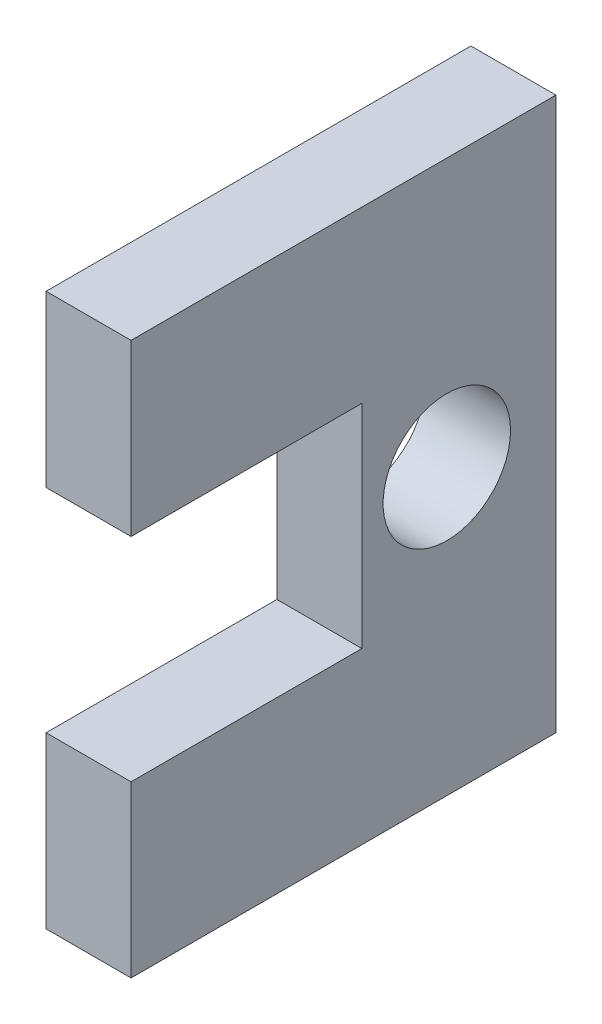
SolidWorks part; units mm, degrees
material "Perspex (TM) GS Acrylic Cast Sheet"
ref_plane "Front Plane" through (0, 0, 0) normal (0, 0, 1) x (1, 0, 0)
ref_plane "Top Plane" through (0, 0, 0) normal (0, 1, 0) x (1, 0, 0)
ref_plane "Right Plane" through (0, 0, 0) normal (1, 0, 0) x (0, 0, -1)
sketch "Sketch1" plane through (0, 0, 0) normal (1, 0, 0) x (0, 0, -1)
  line L0 (0.4324, -6.9715) -> (-5, -6.9715)
  line L1 (5, -10.9715) -> (-5, -10.9715)
  line L2 (5, -10.9715) -> (5, 2.027)
  line L4 (-5, -10.9715) -> (-5, -6.9715)
  line L6 (-5, -1.973) -> (-5, 2.027)
  line L7 (0.4324, -6.9715) -> (0.4324, -1.973)
  line L8 (0.4324, -1.973) -> (-5, -1.973)
  line L12 (5, 2.027) -> (-5, 2.027)
  circle A0 centre (2.4324, -4.273) radius 1.5
  point P0 (0, 0)
  point P8 (-3.0665, -4.4722)
  dimension "D6" = 3
  dimension "D1" = 10
  dimension "D2" = 4
  dimension "D3" = 2.3
  dimension "D4" = 4
  dimension "D5" = 12.9985
extrude "Boss-Extrude1" add sketch "Sketch1" along normal blind 2
